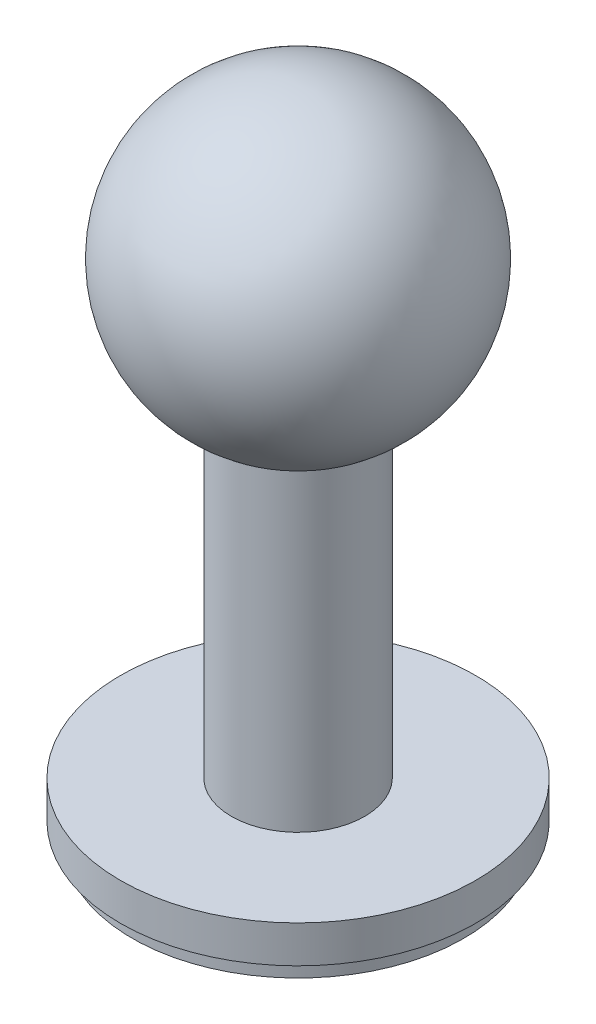
SolidWorks part; units mm, degrees
ref_plane "Front Plane" through (0, 0, 0) normal (0, 0, 1) x (1, 0, 0)
ref_plane "Top Plane" through (0, 0, 0) normal (0, 1, 0) x (1, 0, 0)
ref_plane "Right Plane" through (0, 0, 0) normal (1, 0, 0) x (0, 0, -1)
sketch "Sketch1" plane through (0, 0, 0) normal (0, 1, 0) x (1, 0, 0)
  circle A0 centre (0, 0) radius 7.5
  dimension "D1" = 15
extrude "Boss-Extrude1" add sketch "Sketch1" along normal blind 1.57
sketch "Sketch2" plane through (0, 1.57, 0) normal (0, 1, 0) x (1, 0, 0)
  circle A0 centre (0, 0) radius 2.815
  dimension "D1" = 5.63
extrude "Boss-Extrude2" add sketch "Sketch2" along normal blind 19
sketch "Sketch3" plane through (0, 20.57, 0) normal (0, 1, 0) x (1, 0, 0)
  line L0 (0, 8.312) -> (0, -16.0573) construction
  line L1 (0, 6.35) -> (0, -6.35)
  arc A0 (0, -6.35) -> (0, 6.35) centre (0, 0) ccw
  dimension "D1" = 6.35
revolve "Revolve1" add sketch "Sketch3" angle 360 about L0
sketch "Sketch4" plane through (0, 0, 0) normal (0, -1, 0) x (1, 0, 0)
  circle A0 centre (0, 0) radius 7
  dimension "D1" = 14
extrude "Boss-Extrude3" add sketch "Sketch4" along normal blind 0.8
ref_point "Point1"
ref_plane "Plane1" through (0, 26.92, 0) normal (0, 1, 0) x (1, 0, 0)
